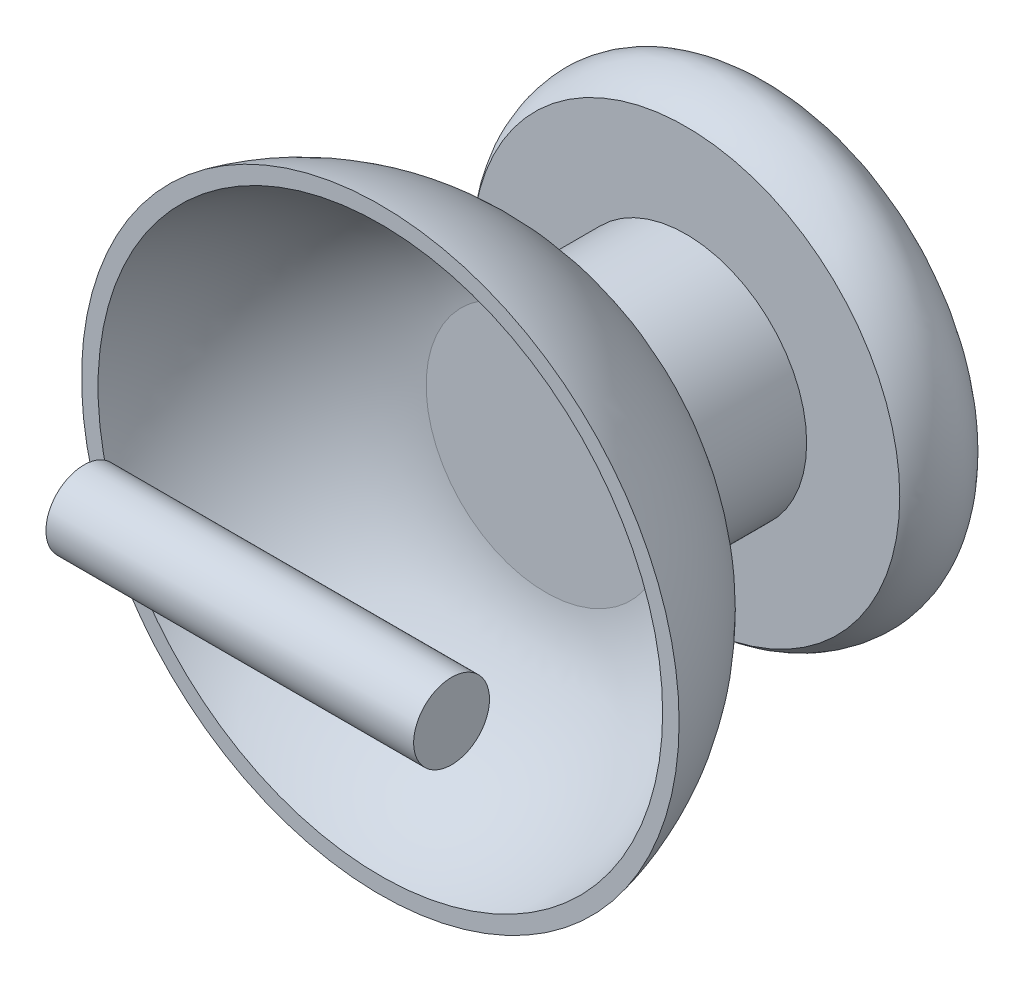
SolidWorks part; units mm, degrees
ref_plane "Front Plane" through (0, 0, 0) normal (0, 0, 1) x (1, 0, 0)
ref_plane "Top Plane" through (0, 0, 0) normal (0, 1, 0) x (1, 0, 0)
ref_plane "Right Plane" through (0, 0, 0) normal (1, 0, 0) x (0, 0, -1)
sketch "Sketch1" plane through (0, 0, 0) normal (0, 1, 0) x (1, 0, 0)
  line L0 (0, 0) -> (0, 48.0203) construction
  line L1 (-13, 0) -> (0, 0)
  line L2 (0, 0) -> (0, 7.9)
  line L3 (0, 7.9) -> (-5.25, 7.9)
  spline S0 degree 3 poles (-5.25, 7.9) (-9.1865, 7.4309) (-12.2357, 3.5838) (-13, 0) knots 0 0 0 0 1 1 1 1
  dimension "D1" = 13
  dimension "D2" = 5.25
  dimension "D3" = 7.9
revolve "Revolve1" add sketch "Sketch1" angle 360 about L0
shell "Shell1" thickness 0.7
sketch "Sketch2" plane through (0, 0, -7.9) normal (0, 0, -1) x (-1, 0, 0)
  circle A0 centre (0, 0) radius 5.25 construction
  circle A1 centre (0, 0) radius 5.25
extrude "Boss-Extrude1" add sketch "Sketch2" along normal blind 5.4
sketch "Sketch3" plane through (0, 0, 0) normal (0, 1, 0) x (1, 0, 0)
  line L0 (0, 0) -> (0, 19.9053) construction
  line L1 (0, 13.3) -> (-9.3, 13.3)
  line L2 (5.25, 13.3) -> (-5.25, 13.3) construction
  line L3 (0, 13.3) -> (0, 18.6)
  spline S0 degree 3 poles (-9.3, 13.3) (-9.7362, 13.755) (-10.2242, 15.1804) (-9.731, 16.3088) (-8.0219, 17.9208) (-3.3891, 18.6) (0, 18.6) knots 0 0 0 0 0.216855 0.411075 0.48939 1 1 1 1
  dimension "D1" = 5.3
  dimension "D2" = 9.3
  dimension "D3" = 10
revolve "Revolve2" add sketch "Sketch3" angle 360 about L0
sketch "Sketch4" plane through (0, 0, 0) normal (1, 0, 0) x (0, 0, -1)
  line L0 (0, 0) -> (-4.9, 0) construction
  circle A0 centre (-4.9, 0) radius 1.65
  dimension "D2" = 3.3
  dimension "D1" = 4.9
extrude "Boss-Extrude2" add sketch "Sketch4" along normal mid plane 16 separate body
equation "\"D1@Sketch1\"=26/2"
equation "\"D2@Sketch3\"=18.6/2"
